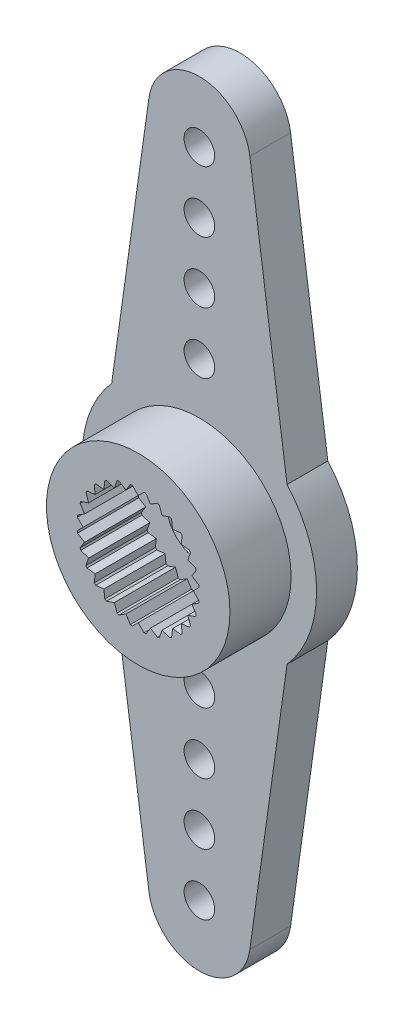
SolidWorks part; units mm, degrees
ref_plane "Plan de face" through (0, 0, 0) normal (0, 0, 1) x (1, 0, 0)
ref_plane "Plan de dessus" through (0, 0, 0) normal (0, 1, 0) x (1, 0, 0)
ref_plane "Plan de droite" through (0, 0, 0) normal (1, 0, 0) x (0, 0, -1)
sketch "Esquisse1" plane through (0, 0, 0) normal (0, 0, 1) x (1, 0, 0)
  circle A0 centre (0, 0) radius 5.75
  circle A1 centre (0, 0) radius 1.6
  dimension "D1" = 11.5
  dimension "D2" = 3.2
extrude "Boss.-Extru.1" add sketch "Esquisse1" along normal blind 5
sketch "Esquisse2" plane through (0, 0, 5) normal (0, 0, 1) x (1, 0, 0)
  circle A0 centre (0, 0) radius 3
  dimension "D1" = 6
extrude "Enlèv. mat.-Extru.1" cut sketch "Esquisse2" against normal blind 3
sketch "Esquisse3" plane through (0, 0, 5) normal (0, 0, 1) x (1, 0, 0)
  circle A0 centre (0, 0) radius 5.75
  circle A1 centre (0, 0) radius 4.5
  circle A2 centre (0, 0) radius 3 construction
  circle A3 centre (0, 0) radius 5.75 construction
  dimension "D1" = 1.5
extrude "Enlèv. mat.-Extru.2" cut sketch "Esquisse3" against normal blind 3
sketch "Esquisse4" plane through (0, 0, 0) normal (0, 0, -1) x (-1, 0, 0)
  line L0 (-4.3, 3.8174) -> (-2.4759, 16.8466)
  line L1 (2.4759, 16.8466) -> (4.3, 3.8174)
  line L2 (-5.2729, 19) -> (6.8365, 19) construction
  line L3 (0, 0) -> (0, 24.2526) construction
  circle A0 centre (0, 0) radius 5.75 construction
  arc A1 (-2.4759, 16.8466) -> (2.4759, 16.8466) centre (0, 16.5) cw
  arc A2 (-4.3, 3.8174) -> (4.3, 3.8174) centre (0, 0) cw
  dimension "D2" = 2.5
  dimension "D1" = 8.6
  dimension "D3" = 19
extrude "Boss.-Extru.2" add sketch "Esquisse4" against normal up to surface (2 mm away) up to face at (4.5, 0, 2)
pattern_circular "Répétition circulaire1" count 2 every 180 about axis through (0, 0, 0) along (0, 0, 1) of "Boss.-Extru.2"
sketch "Esquisse5" plane through (0, 0, 0) normal (0, 0, -1) x (-1, 0, 0)
  line L0 (0, 0) -> (0, 20.4605) construction
  circle A0 centre (0, 7) radius 0.75
  circle A1 centre (0, 10) radius 0.75
  circle A2 centre (0, 13) radius 0.75
  circle A3 centre (0, 16) radius 0.75
  dimension "D5" = 1.5
  dimension "D6" = 1.5
  dimension "D7" = 1.5
  dimension "D8" = 1.5
  dimension "D1" = 7
  dimension "D2" = 3
  dimension "D3" = 3
  dimension "D4" = 3
extrude "Enlèv. mat.-Extru.3" cut sketch "Esquisse5" against normal blind 3
pattern_circular "Répétition circulaire2" count 2 every 180 about axis through (0, 0, 0) along (0, 0, 1) of "Enlèv. mat.-Extru.3"
sketch "Esquisse6" plane through (0, 0, 5) normal (0, 0, 1) x (1, 0, 0)
  line L0 (-1.598, 3) -> (1.8482, 3) construction
  line L1 (0, 0) -> (0, 5.9454) construction
  line L2 (-0.3, 3) -> (0, 2.7)
  line L3 (0, 2.7) -> (0.3, 3)
  line L4 (0.3, 3) -> (-0.3, 3)
  circle A0 centre (0, 0) radius 3 construction
  dimension "D1" = 0.3
  dimension "D2" = 0.6
extrude "Boss.-Extru.3" add sketch "Esquisse6" against normal up to surface (3 mm away) up to face at (1.6, 0, 2)
pattern_circular "Répétition circulaire3" count 28 over 360 about axis through (0, 0, 0) along (0, 0, 1) of "Boss.-Extru.3"
sketch "Esquisse7" plane through (0, 0, 0) normal (0, 0, -1) x (-1, 0, 0)
  circle A0 centre (0, 0) radius 1.6
  circle A1 centre (0, 0) radius 3
  circle A2 centre (0, 0) radius 1.6 construction
  dimension "D1" = 6
extrude "Enlèv. mat.-Extru.4" cut sketch "Esquisse7" against normal blind 1
sketch "Esquisse8" plane through (0, 0, 0) normal (0, 0, -1) x (-1, 0, 0)
  circle A0 centre (0, 0) radius 3.4
  circle A1 centre (0, 0) radius 4.7
  circle A2 centre (0, 0) radius 3 construction
  dimension "D1" = 0.4
  dimension "D2" = 1.3
extrude "Enlèv. mat.-Extru.5" cut sketch "Esquisse8" against normal blind 1
ref_plane "Plane1" through (0, 0, 0) normal (0, 0, -1) x (-1, 0, 0)
sketch "Sketch1" plane through (0, 0, 0) normal (0, 0, -1) x (-1, 0, 0)
  line L0 (-2.4759, 16.8466) -> (-4.3, 3.8174)
  line L1 (2.4759, 16.8466) -> (4.3, 3.8174)
  line L2 (-4.3, -3.8174) -> (-2.4759, -16.8466)
  line L3 (4.3, -3.8174) -> (2.4759, -16.8466)
  arc A0 (4.3, 3.8174) -> (4.3, -3.8174) centre (0, 0) cw
  arc A1 (-4.3, 3.8174) -> (-4.3, -3.8174) centre (0, 0) ccw
  arc A2 (-2.4759, 16.8466) -> (2.4759, 16.8466) centre (0, 16.5) cw
  arc A3 (-2.4759, -16.8466) -> (2.4759, -16.8466) centre (0, -16.5) ccw
